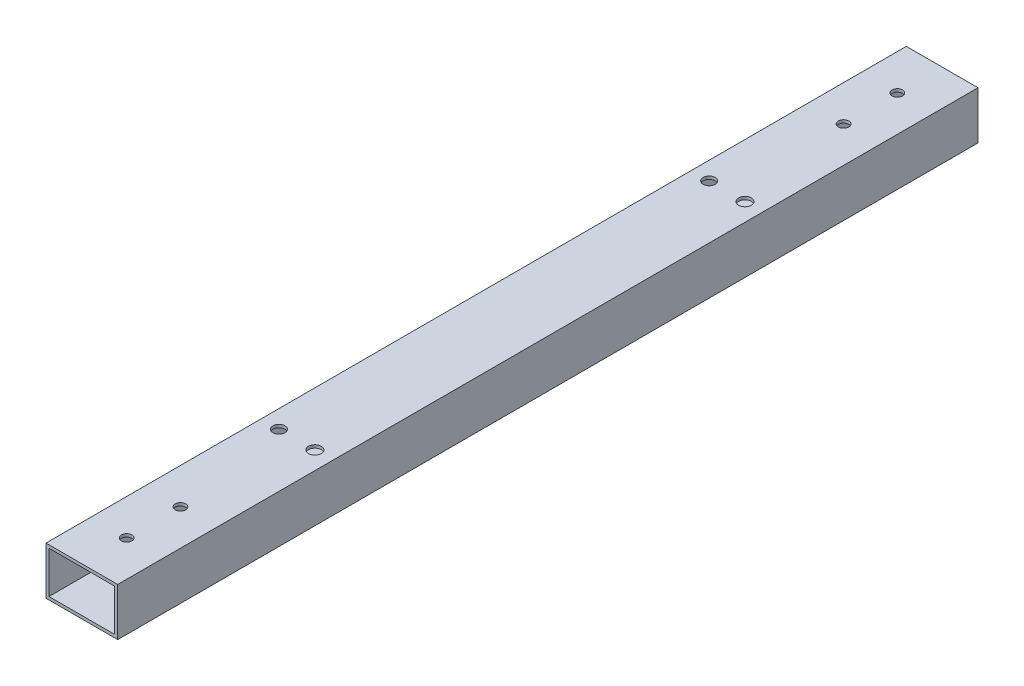
SolidWorks part; units mm, degrees
ref_plane "Front Plane" through (0, 0, 0) normal (0, 0, 1) x (1, 0, 0)
ref_plane "Top Plane" through (0, 0, 0) normal (0, 1, 0) x (1, 0, 0)
ref_plane "Right Plane" through (0, 0, 0) normal (1, 0, 0) x (0, 0, -1)
sketch "Sketch1" plane through (0, 0, 0) normal (0, 0, 1) x (1, 0, 0)
  line L0 (38.1, 0) -> (34.925, 0) construction
  line L1 (-38.1, 0) -> (38.1, 0) construction
  line L2 (0, 25.4) -> (0, -25.4)
  point P7 (0, 0)
sketch "Sketch2" plane through (0, 0, 0) normal (1, 0, 0) x (0, 0, -1)
  line L0 (457.2, 0) -> (-457.2, 0)
  point P4 (0, 0)
  dimension "Length" = 914.4
sketch "Sketch3" plane through (0, 0, 0) normal (0, 0, 1) x (1, 0, 0)
  line L0 (-38.1, 0) -> (38.1, 0) construction
  line L5 (38.1, -25.4) -> (-38.1, -25.4)
  line L6 (38.1, -25.4) -> (38.1, 25.4)
  line L11 (38.1, 25.4) -> (-38.1, 25.4)
  line L12 (-38.1, -25.4) -> (-38.1, 25.4)
  line L14 (38.1, -25.4) -> (-38.1, 25.4) construction
  line L15 (38.1, 25.4) -> (-38.1, -25.4) construction
  line L16 (34.925, -22.225) -> (-34.925, -22.225)
  line L17 (34.925, -22.225) -> (34.925, 22.225)
  line L18 (34.925, 22.225) -> (-34.925, 22.225)
  line L19 (-34.925, -22.225) -> (-34.925, 22.225)
  line L20 (34.925, -22.225) -> (-34.925, 22.225) construction
  line L21 (34.925, 22.225) -> (-34.925, -22.225) construction
  point P0 (0, 0)
  point P5 (0, 0)
  point P13 (34.925, -25.4)
  dimension "D1" = 3.175
  dimension "D3" = 76.2
  dimension "D4" = 50.8
  dimension "D2" = 3.175
extrude "Boss-Extrude1" add sketch "Sketch3" along normal up to vertex (457.2 mm away) and the other way up to vertex (457.2 mm away) up to point (0, 0, 457.2) other way up to point (0, 0, -457.2)
sketch "Sketch5" plane through (0, 0, 0) normal (1, 0, 0) x (0, 0, -1)
  line L0 (-457.2, 0) -> (457.2, 0) construction
  line L3 (-457.2, -25.4) -> (-457.2, 25.4) construction
  line L4 (457.2, -25.4) -> (457.2, 25.4) construction
  point P6 (-371.475, 0)
  point P7 (-342.9, 0)
  point P8 (342.9, 0)
  point P10 (371.475, 0)
  dimension "D1" = 85.725
  dimension "D2" = 114.3
  dimension "D3" = 85.725
  dimension "D4" = 114.3
sketch "Sketch6" plane through (0, 25.4, 0) normal (0, 1, 0) x (1, 0, 0)
  line L0 (-38.1, 0) -> (38.1, 0) construction
  line L1 (-38.1, -457.2) -> (-38.1, 457.2) construction
  line L2 (38.1, -457.2) -> (38.1, 457.2) construction
  line L3 (0, 457.2) -> (0, -457.2) construction
  line L4 (38.1, 457.2) -> (-38.1, 457.2) construction
  line L5 (38.1, -457.2) -> (-38.1, -457.2) construction
  line L6 (-38.1, -228.6) -> (38.1, -228.6) construction
  line L8 (-19.05, -431.8) -> (19.05, -431.8)
  line L9 (-19.05, -431.8) -> (-19.05, -330.2)
  line L10 (-19.05, -330.2) -> (19.05, -330.2)
  line L11 (19.05, -431.8) -> (19.05, -330.2)
  line L12 (-19.05, -431.8) -> (19.05, -330.2) construction
  line L13 (-19.05, -330.2) -> (19.05, -431.8) construction
  circle A0 centre (-19.05, -228.6) radius 6.3949
  circle A1 centre (19.05, -228.6) radius 6.7896
  circle A2 centre (19.05, 228.6) radius 6.7896
  circle A3 centre (-19.05, 228.6) radius 6.3949
  circle A4 centre (0, -352.425) radius 5.5626
  circle A5 centre (0, -409.575) radius 5.5626
  circle A6 centre (0, 409.575) radius 5.5626
  circle A7 centre (0, 352.425) radius 5.5626
  point P22 (0, -381)
  dimension "D6" = 11.1252
  dimension "D7" = 11.1252
  dimension "D1" = 228.6
  dimension "D2" = 38.1
  dimension "D3" = 19.05
  dimension "D4" = 101.6
  dimension "D5" = 38.1
  dimension "D8" = 22.225
  dimension "D9" = 57.15
  dimension "D10" = 25.4
extrude "Cut-Extrude1" cut sketch "Sketch6" against normal through all contours A4 | A5 | A6 | A7 | A0 | A1 | A3 | A2
sketch "Sketch7" plane through (-38.1, 0, 0) normal (-1, 0, 0) x (0, 0, 1)
  line L0 (-457.2, 0) -> (457.2, 0) construction
  line L1 (-457.2, 25.4) -> (-457.2, -25.4) construction
  line L2 (457.2, 25.4) -> (457.2, -25.4) construction
  line L3 (0, 25.4) -> (0, -25.4) construction
  line L4 (457.2, 25.4) -> (-457.2, 25.4) construction
  line L5 (457.2, -25.4) -> (-457.2, -25.4) construction
  line L7 (330.2, -19.05) -> (431.8, -19.05)
  line L8 (330.2, -19.05) -> (330.2, 19.05)
  line L9 (330.2, 19.05) -> (431.8, 19.05)
  line L10 (431.8, -19.05) -> (431.8, 19.05)
  line L11 (330.2, -19.05) -> (431.8, 19.05) construction
  line L12 (330.2, 19.05) -> (431.8, -19.05) construction
  circle A0 centre (352.425, 0) radius 5.5626
  circle A1 centre (409.575, 0) radius 5.5626
  circle A2 centre (-409.575, 0) radius 5.5626
  circle A3 centre (-352.425, 0) radius 5.5626
  point P12 (381, 0)
  dimension "D4" = 11.1252
  dimension "D5" = 11.1252
  dimension "D1" = 101.6
  dimension "D2" = 38.1
  dimension "D3" = 25.4
  dimension "D6" = 22.225
  dimension "D7" = 57.15
extrude "Cut-Extrude2" [suppressed] cut sketch "Sketch7" against normal through all contours A0 | A1 | A2 | A3
sketch "Sketch8" plane through (0, -25.4, 0) normal (0, -1, 0) x (1, 0, 0)
  line L0 (0, -457.2) -> (0, 457.2) construction
  line L1 (-38.1, -457.2) -> (38.1, -457.2) construction
  line L2 (-38.1, 457.2) -> (38.1, 457.2) construction
  circle A0 centre (0, 0) radius 15.875
extrude "Cut-Extrude3" [suppressed] cut sketch "Sketch8" against normal through all
equation "\"D1@Sketch3\"=\"Wall thickness@Sketch1\""
equation "\"D1@Sketch5\"=\"Width@Sketch1\"*1.125"
equation "\"D2@Sketch5\"=\"Width@Sketch1\"*1.5"
equation "\"D3@Sketch5\"=\"D1@Sketch5\""
equation "\"D4@Sketch5\"=\"D2@Sketch5\""
equation "\"D2@Sketch3\"=\"Wall Thickness@Sketch1\""
